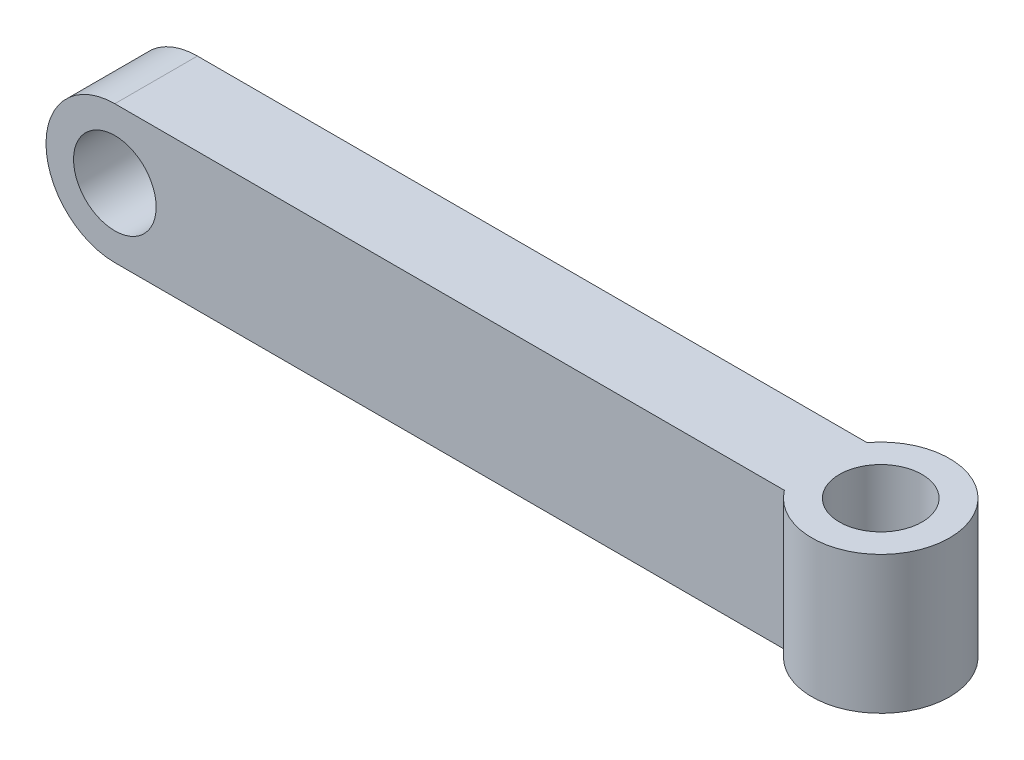
SolidWorks part; units mm, degrees
ref_plane "前视基准面" through (0, 0, 0) normal (0, 0, 1) x (1, 0, 0)
ref_plane "上视基准面" through (0, 0, 0) normal (0, 1, 0) x (1, 0, 0)
ref_plane "右视基准面" through (0, 0, 0) normal (1, 0, 0) x (0, 0, -1)
other "Configuration Table"
sketch "草图1" plane through (0, 0, 0) normal (0, 0, 1) x (1, 0, 0)
  line L0 (0, 0) -> (50000, 0) construction
  line L1 (0, 0) -> (0, 50000) construction
  line L3 (-31.32, 5) -> (31.32, 5)
  line L4 (-31.32, 5) -> (-31.32, -5)
  line L5 (-31.32, -5) -> (31.32, -5)
  line L6 (31.32, 5) -> (31.32, -5)
extrude "凸台-拉伸2" add sketch "草图1" along normal blind 10
sketch "草图3" plane through (0, 5, 0) normal (0, 1, 0) x (1, 0, 0)
  line L0 (31.32, -10) -> (31.32, 0) construction
  line L1 (-5.5, 0) -> (5.5, 0) construction
  line L2 (26.32, -10) -> (31.32, -10)
  line L3 (31.32, -10) -> (31.32, 0)
  line L4 (31.32, 0) -> (26.32, 0)
  circle A0 centre (26.32, -5) radius 5
  circle A1 centre (26.32, -5) radius 3
  line M2 (31.32, 0) -> (-31.32, 0)
  line M4 (-31.32, -10) -> (31.32, -10)
  line M5 (31.32, -10) -> (31.32, 0)
extrude "切除-拉伸3" cut sketch "草图3" against normal through all contours A0 M4 M5 | A0 L3 M2 | A1
sketch "草图4" plane through (0, 0, 10) normal (0, 0, 1) x (1, 0, 0)
  line L0 (26.32, 5) -> (-31.32, 5) construction
  line L1 (-31.32, 5) -> (-31.32, -5) construction
  line L2 (-26.32, 5) -> (-31.32, 5)
  line L3 (-31.32, 5) -> (-31.32, -5)
  line L4 (-31.32, -5) -> (-26.32, -5)
  circle A0 centre (-26.32, 0) radius 5
  circle A1 centre (-26.32, 0) radius 3
  line M2 (-31.32, -5) -> (26.32, -5)
  line M4 (26.32, 5) -> (-31.32, 5)
  line M5 (-31.32, 5) -> (-31.32, -5)
extrude "切除-拉伸5" cut sketch "草图4" against normal through all contours A0 M4 M5 | A0 L3 M2 | A1
sketch "草图5" plane through (0, 5, 0) normal (0, 1, 0) x (1, 0, 0)
  line L0 (25.32, -5.2323) -> (25.32, 49994.7677) construction
  line L1 (25.32, -8) -> (-26.32, -8)
  line L2 (-26.32, 0) -> (-26.32, -10) construction
  line L3 (25.32, -2) -> (-26.32, -2)
  line L4 (-26.32, -5) -> (49973.68, -5) construction
  line L5 (26.32, -10) -> (-26.32, -10) construction
  line L6 (25.32, -2) -> (25.32, -8)
  line L7 (-26.32, -2) -> (-26.32, -8)
  line L8 (-21.32, -2) -> (-21.32, -8)
  line L9 (-21.32, -2) -> (-21.32, 0)
  line L10 (-21.32, 0) -> (25.32, 0)
  line L11 (25.32, 0) -> (25.32, -10.0276)
  line L12 (25.32, -10.0276) -> (-21.32, -10)
  line L13 (-21.32, -10) -> (-21.32, -8)
  line L14 (23.32, 0.0264) -> (23.32, -10.0264)
  circle A0 centre (26.32, -5) radius 3
  point P10 (-26.32, -5)
  point P26 (23.32, -5)
  line M10 (-26.32, -10) -> (26.32, -10)
  dimension "D1" = 2
  dimension "D2" = 5
extrude "切除-拉伸7" cut sketch "草图5" against normal through all contours L14 L1 L13 M10 | L14 L10 L9 L3
sketch "草图6" plane through (0, 5, 0) normal (0, 1, 0) x (1, 0, 0)
  line L0 (23.32, -9) -> (23.32, -10)
  line L1 (23.32, -8) -> (23.32, -10) construction
  line L2 (23.32, -10) -> (26.32, -10)
  line L3 (23.32, -1) -> (23.32, 0)
  line L4 (23.32, 0) -> (23.32, -2) construction
  line L5 (-5.5, 0) -> (5.5, 0) construction
  line L6 (23.32, 0) -> (26.32, 0)
  circle A0 centre (26.32, -5) radius 5
  line M2 (23.32, -8) -> (23.32, -10)
  line M3 (23.32, -10) -> (26.32, -10)
  line M5 (26.32, 0) -> (23.32, 0)
  line M6 (23.32, 0) -> (23.32, -2)
extrude "切除-拉伸8" cut sketch "草图6" against normal through all contours A0 M5 M6 | A0 M2 M3
sketch "草图10" plane through (0, 5, 0) normal (0, 1, 0) x (1, 0, 0)
  circle A0 centre (26.32, -5) radius 5
  circle A1 centre (26.32, -5) radius 3
  circle M2 centre (26.32, -5) radius 3
  arc M3 (23.32, -9) -> (23.32, -1) centre (26.32, -5) ccw
  line M4 (23.32, -1) -> (23.32, -2)
  line M5 (23.32, -2) -> (-21.32, -2)
  line M11 (-21.32, -8) -> (23.32, -8)
  line M12 (23.32, -8) -> (23.32, -9)
extrude "凸台-拉伸7" add sketch "草图10" against normal blind 10 contours A0 M5 M11 M12 M3 M4 M2
sketch "草图11" plane through (0, 5, 0) normal (0, 1, 0) x (1, 0, 0)
  line L0 (-26.32, -5) -> (49973.68, -5) construction
  line L1 (-26.32, 0) -> (-26.32, -10) construction
  line L2 (26.32, -5) -> (26.32, 49995) construction
  circle A0 centre (26.32, -5) radius 3
  point P4 (-26.32, -5)
extrude "切除-拉伸9" cut sketch "草图11" against normal through all
sketch "草图13" plane through (-21.32, 0, 0) normal (1, 0, 0) x (0, 0, -1)
  line L1 (-10, 5) -> (-8, 5)
  line L2 (-10, 5) -> (-10, -5)
  line L3 (-10, -5) -> (-8, -5)
  line L4 (-8, 5) -> (-8, -5)
  line L5 (-2, 5) -> (0, 5)
  line L6 (-2, 5) -> (-2, -5)
  line L7 (-2, -5) -> (0, -5)
  line L8 (0, 5) -> (0, -5)
extrude "切除-拉伸11" cut sketch "草图13" against normal through all
